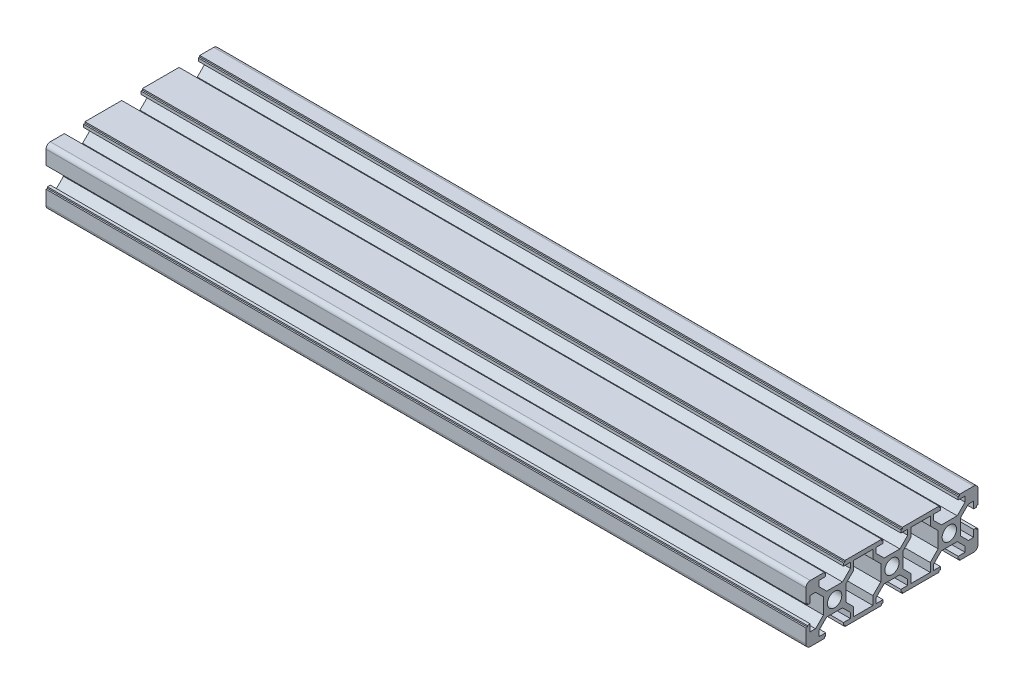
SolidWorks part; units mm, degrees
ref_plane "前视基准面" through (0, 0, 0) normal (0, 0, 1) x (1, 0, 0)
ref_plane "上视基准面" through (0, 0, 0) normal (0, 1, 0) x (1, 0, 0)
ref_plane "右视基准面" through (0, 0, 0) normal (1, 0, 0) x (0, 0, -1)
sketch "草图5" plane through (0, 0, 0) normal (0, 0, 1) x (1, 0, 0)
  line L0 (548.6373, 8.9854) -> (813.6373, 8.9854)
  dimension "D1" = 265
other "铝型材 20 X 20 X R1.5(1)"
ref_plane "基准面2" through (548.6373, 8.9854, 0) normal (1, 0, 0) x (0, 1, 0)
sketch "Sketch1" plane through (548.6373, 8.9854, 0) normal (1, 0, 0) x (0, 1, 0)
  line L0 (-10, -3.6) -> (-9.5, -3.6)
  line L1 (-9.5, -3.6) -> (-9.5, -3.1)
  line L2 (-9.5, -3.1) -> (-8.5, -3.1)
  line L3 (-8.5, -3.1) -> (-8.5, -5.5)
  line L4 (10, -8.5) -> (10, -3.6)
  line L5 (8.5, -10) -> (3.6, -10)
  line L6 (-10, 8.5) -> (-10, 3.6)
  line L7 (-10, 11.5) -> (-10, 8.5)
  line L8 (-14.8756, 0) -> (0, 0) construction
  line L9 (0, 0) -> (0, 14.1675) construction
  line L10 (-8.5, -5.5) -> (-6.65, -5.5)
  line L11 (-6.65, -5.5) -> (-3.9, -2.75)
  line L12 (-3.9, -2.75) -> (-3.9, 2.75)
  line L13 (-6.65, 5.5) -> (-3.9, 2.75)
  line L14 (-8.5, 5.5) -> (-6.65, 5.5)
  line L15 (-8.5, 3.1) -> (-8.5, 5.5)
  line L16 (-9.5, 3.1) -> (-8.5, 3.1)
  line L17 (-9.5, 3.6) -> (-9.5, 3.1)
  line L18 (-10, 3.6) -> (-9.5, 3.6)
  line L19 (-10, -3.6) -> (-10, -8.5)
  line L20 (-5.5, 6.65) -> (-8.5, 6.65)
  line L21 (-8.5, 6.65) -> (-8.5, 13.35)
  line L22 (-8.5, 13.35) -> (-5.5, 13.35)
  line L23 (-5.5, 26.65) -> (-8.5, 26.65)
  line L24 (-8.5, 26.65) -> (-8.5, 33.35)
  line L25 (-5.5, 6.65) -> (-2.75, 3.9)
  line L26 (-2.75, 3.9) -> (2.75, 3.9)
  line L27 (5.5, 6.65) -> (2.75, 3.9)
  line L28 (-8.5, 33.35) -> (-5.5, 33.35)
  line L29 (5.5, 6.65) -> (8.5, 6.65)
  line L30 (8.5, 6.65) -> (8.5, 13.35)
  line L31 (8.5, 13.35) -> (5.5, 13.35)
  line L32 (5.5, 26.65) -> (8.5, 26.65)
  line L33 (10, 3.6) -> (9.5, 3.6)
  line L34 (9.5, 3.6) -> (9.5, 3.1)
  line L35 (9.5, 3.1) -> (8.5, 3.1)
  line L36 (8.5, 3.1) -> (8.5, 5.5)
  line L37 (8.5, 5.5) -> (6.65, 5.5)
  line L38 (6.65, 5.5) -> (3.9, 2.75)
  line L39 (3.9, 2.75) -> (3.9, -2.75)
  line L40 (6.65, -5.5) -> (3.9, -2.75)
  line L41 (8.5, -5.5) -> (6.65, -5.5)
  line L42 (8.5, -3.1) -> (8.5, -5.5)
  line L43 (9.5, -3.1) -> (8.5, -3.1)
  line L44 (9.5, -3.6) -> (9.5, -3.1)
  line L45 (10, -3.6) -> (9.5, -3.6)
  line L46 (3.6, -10) -> (3.6, -9.5)
  line L47 (3.6, -9.5) -> (3.1, -9.5)
  line L48 (3.1, -9.5) -> (3.1, -8.5)
  line L49 (3.1, -8.5) -> (5.5, -8.5)
  line L50 (5.5, -8.5) -> (5.5, -6.65)
  line L51 (5.5, -6.65) -> (2.75, -3.9)
  line L52 (2.75, -3.9) -> (-2.75, -3.9)
  line L53 (-5.5, -6.65) -> (-2.75, -3.9)
  line L54 (-5.5, -8.5) -> (-5.5, -6.65)
  line L55 (-3.1, -8.5) -> (-5.5, -8.5)
  line L56 (-3.1, -9.5) -> (-3.1, -8.5)
  line L57 (-3.6, -9.5) -> (-3.1, -9.5)
  line L58 (-3.6, -10) -> (-3.6, -9.5)
  line L59 (10, 3.6) -> (10, 8.5)
  line L60 (-3.6, -10) -> (-8.5, -10)
  line L61 (-10, 31.5) -> (-10, 28.5)
  line L62 (-10, 16.4) -> (-9.5, 16.4)
  line L63 (-9.5, 16.4) -> (-9.5, 16.9)
  line L64 (-9.5, 16.9) -> (-8.5, 16.9)
  line L65 (-8.5, 16.9) -> (-8.5, 14.5)
  line L66 (10, 11.5) -> (10, 16.4)
  line L67 (10, 31.5) -> (10, 28.5)
  line L68 (-10, 28.5) -> (-10, 23.6)
  line L69 (10, 11.5) -> (10, 8.5)
  line L70 (-8.5, 14.5) -> (-6.65, 14.5)
  line L71 (-6.65, 14.5) -> (-3.9, 17.25)
  line L72 (-3.9, 17.25) -> (-3.9, 22.75)
  line L73 (-6.65, 25.5) -> (-3.9, 22.75)
  line L74 (-8.5, 25.5) -> (-6.65, 25.5)
  line L75 (-8.5, 23.1) -> (-8.5, 25.5)
  line L76 (-9.5, 23.1) -> (-8.5, 23.1)
  line L77 (-9.5, 23.6) -> (-9.5, 23.1)
  line L78 (-10, 23.6) -> (-9.5, 23.6)
  line L79 (-10, 16.4) -> (-10, 11.5)
  line L80 (8.5, 26.65) -> (8.5, 33.35)
  line L81 (8.5, 33.35) -> (5.5, 33.35)
  line L85 (-5.5, 26.65) -> (-2.75, 23.9)
  line L86 (-2.75, 23.9) -> (2.75, 23.9)
  line L87 (5.5, 26.65) -> (2.75, 23.9)
  line L93 (10, 23.6) -> (9.5, 23.6)
  line L94 (9.5, 23.6) -> (9.5, 23.1)
  line L95 (9.5, 23.1) -> (8.5, 23.1)
  line L96 (8.5, 23.1) -> (8.5, 25.5)
  line L97 (8.5, 25.5) -> (6.65, 25.5)
  line L98 (6.65, 25.5) -> (3.9, 22.75)
  line L99 (3.9, 22.75) -> (3.9, 17.25)
  line L100 (6.65, 14.5) -> (3.9, 17.25)
  line L101 (8.5, 14.5) -> (6.65, 14.5)
  line L102 (8.5, 16.9) -> (8.5, 14.5)
  line L103 (9.5, 16.9) -> (8.5, 16.9)
  line L104 (9.5, 16.4) -> (9.5, 16.9)
  line L105 (10, 16.4) -> (9.5, 16.4)
  line L111 (5.5, 13.35) -> (2.75, 16.1)
  line L112 (2.75, 16.1) -> (-2.75, 16.1)
  line L113 (-5.5, 13.35) -> (-2.75, 16.1)
  line L119 (10, 23.6) -> (10, 28.5)
  line L122 (-14.8756, 20) -> (0, 20) construction
  line L123 (0, 20) -> (0, 34.1675) construction
  line L124 (-10, 36.4) -> (-9.5, 36.4)
  line L125 (-9.5, 36.4) -> (-9.5, 36.9)
  line L126 (-9.5, 36.9) -> (-8.5, 36.9)
  line L127 (-8.5, 36.9) -> (-8.5, 34.5)
  line L128 (10, 31.5) -> (10, 36.4)
  line L130 (-10, 48.5) -> (-10, 43.6)
  line L131 (-8.5, 50) -> (-3.6, 50)
  line L132 (-8.5, 34.5) -> (-6.65, 34.5)
  line L133 (-6.65, 34.5) -> (-3.9, 37.25)
  line L134 (-3.9, 37.25) -> (-3.9, 42.75)
  line L135 (-6.65, 45.5) -> (-3.9, 42.75)
  line L136 (-8.5, 45.5) -> (-6.65, 45.5)
  line L137 (-8.5, 43.1) -> (-8.5, 45.5)
  line L138 (-9.5, 43.1) -> (-8.5, 43.1)
  line L139 (-9.5, 43.6) -> (-9.5, 43.1)
  line L140 (-10, 43.6) -> (-9.5, 43.6)
  line L141 (-10, 36.4) -> (-10, 31.5)
  line L142 (-3.6, 50) -> (-3.6, 49.5)
  line L143 (-3.6, 49.5) -> (-3.1, 49.5)
  line L144 (-3.1, 49.5) -> (-3.1, 48.5)
  line L145 (-3.1, 48.5) -> (-5.5, 48.5)
  line L146 (-5.5, 48.5) -> (-5.5, 46.65)
  line L147 (-5.5, 46.65) -> (-2.75, 43.9)
  line L148 (-2.75, 43.9) -> (2.75, 43.9)
  line L149 (5.5, 46.65) -> (2.75, 43.9)
  line L150 (5.5, 48.5) -> (5.5, 46.65)
  line L151 (3.1, 48.5) -> (5.5, 48.5)
  line L152 (3.1, 49.5) -> (3.1, 48.5)
  line L153 (3.6, 49.5) -> (3.1, 49.5)
  line L154 (3.6, 50) -> (3.6, 49.5)
  line L155 (10, 43.6) -> (9.5, 43.6)
  line L156 (9.5, 43.6) -> (9.5, 43.1)
  line L157 (9.5, 43.1) -> (8.5, 43.1)
  line L158 (8.5, 43.1) -> (8.5, 45.5)
  line L159 (8.5, 45.5) -> (6.65, 45.5)
  line L160 (6.65, 45.5) -> (3.9, 42.75)
  line L161 (3.9, 42.75) -> (3.9, 37.25)
  line L162 (6.65, 34.5) -> (3.9, 37.25)
  line L163 (8.5, 34.5) -> (6.65, 34.5)
  line L164 (8.5, 36.9) -> (8.5, 34.5)
  line L165 (9.5, 36.9) -> (8.5, 36.9)
  line L166 (9.5, 36.4) -> (9.5, 36.9)
  line L167 (10, 36.4) -> (9.5, 36.4)
  line L173 (5.5, 33.35) -> (2.75, 36.1)
  line L174 (2.75, 36.1) -> (-2.75, 36.1)
  line L175 (-5.5, 33.35) -> (-2.75, 36.1)
  line L181 (10, 43.6) -> (10, 48.5)
  line L183 (3.6, 50) -> (8.5, 50)
  line L184 (-14.8756, 40) -> (0, 40) construction
  line L185 (0, 40) -> (0, 54.1675) construction
  line L186 (-3.6, 10) -> (-8.5, 10) [skipped]
  line L187 (-3.6, 30) -> (-8.5, 30) [skipped]
  line L188 (8.5, 10) -> (3.6, 10) [skipped]
  line L189 (8.5, 30) -> (3.6, 30) [skipped]
  line L190 (-3.6, 10) -> (-3.6, 9.5) [skipped]
  line L191 (-3.6, 9.5) -> (-3.1, 9.5) [skipped]
  line L192 (-3.1, 9.5) -> (-3.1, 8.5) [skipped]
  line L193 (-3.1, 10.5) -> (-3.1, 11.5) [skipped]
  line L194 (-3.6, 10.5) -> (-3.1, 10.5) [skipped]
  line L195 (-3.6, 10) -> (-3.6, 10.5) [skipped]
  line L196 (-3.1, 11.5) -> (-5.5, 11.5) [skipped]
  line L197 (-3.1, 8.5) -> (-5.5, 8.5) [skipped]
  line L198 (-5.5, 8.5) -> (-5.5, 6.65) [skipped]
  line L199 (-5.5, 11.5) -> (-5.5, 13.35) [skipped]
  line L200 (-5.5, 31.5) -> (-5.5, 33.35) [skipped]
  line L201 (-3.1, 31.5) -> (-5.5, 31.5) [skipped]
  line L202 (-3.1, 30.5) -> (-3.1, 31.5) [skipped]
  line L203 (-3.6, 30.5) -> (-3.1, 30.5) [skipped]
  line L204 (-3.6, 30) -> (-3.6, 30.5) [skipped]
  line L205 (5.5, 8.5) -> (5.5, 6.65) [skipped]
  line L206 (3.1, 8.5) -> (5.5, 8.5) [skipped]
  line L207 (3.1, 9.5) -> (3.1, 8.5) [skipped]
  line L208 (3.6, 9.5) -> (3.1, 9.5) [skipped]
  line L209 (3.6, 10) -> (3.6, 9.5) [skipped]
  line L210 (3.6, 10) -> (3.6, 10.5) [skipped]
  line L211 (3.6, 10.5) -> (3.1, 10.5) [skipped]
  line L212 (3.1, 10.5) -> (3.1, 11.5) [skipped]
  line L213 (3.1, 11.5) -> (5.5, 11.5) [skipped]
  line L214 (5.5, 11.5) -> (5.5, 13.35) [skipped]
  line L215 (3.6, 30) -> (3.6, 30.5) [skipped]
  line L216 (3.6, 30.5) -> (3.1, 30.5) [skipped]
  line L217 (3.1, 30.5) -> (3.1, 31.5) [skipped]
  line L218 (3.1, 31.5) -> (5.5, 31.5) [skipped]
  line L219 (5.5, 31.5) -> (5.5, 33.35) [skipped]
  circle A0 centre (0, 0) radius 2.5
  arc A1 (-8.5, -10) -> (-10, -8.5) centre (-8.5, -8.5) cw
  arc A3 (10, -8.5) -> (8.5, -10) centre (8.5, -8.5) cw
  circle A5 centre (0, 20) radius 2.5
  circle A10 centre (0, 40) radius 2.5
  arc A12 (-8.5, 50) -> (-10, 48.5) centre (-8.5, 48.5) ccw
  arc A14 (10, 48.5) -> (8.5, 50) centre (8.5, 48.5) ccw
  arc A15 (-8.5, 10) -> (-10, 11.5) centre (-8.5, 11.5) cw [skipped]
  arc A16 (-8.5, 30) -> (-10, 31.5) centre (-8.5, 31.5) cw [skipped]
  arc A17 (10, 11.5) -> (8.5, 10) centre (8.5, 11.5) cw [skipped]
  arc A18 (10, 31.5) -> (8.5, 30) centre (8.5, 31.5) cw [skipped]
  point P0 (0, 0)
  point P1 (0, 10)
  point P2 (-10, 0)
  point P3 (0, 0)
  point P4 (0, 0)
  point P5 (10, -10)
  point P6 (10, 10)
  point P7 (-10, 10)
  point P8 (-10, -10)
  point P13 (0, 0)
  point P36 (-10, -10)
  point P39 (-10, 10)
  point P44 (0, 20)
  point P87 (0, 30)
  point P88 (-10, 20)
  point P89 (0, 20)
  point P90 (0, 20)
  point P91 (10, 10)
  point P92 (10, 30)
  point P93 (-10, 30)
  point P94 (-10, 10)
  point P99 (0, 20)
  point P168 (0, 40)
  point P169 (0, 50)
  point P170 (-10, 40)
  point P171 (0, 40)
  point P172 (0, 40)
  point P173 (10, 30)
  point P174 (10, 50)
  point P175 (-10, 50)
  point P176 (-10, 30)
  point P181 (0, 40)
  dimension "D1" = 11
  dimension "D3" = 6.2
  dimension "D4" = 7.2
  dimension "D5" = 6.1
  dimension "D6" = 5
  dimension "D7" = 1.5
  dimension "D8" = 45
  dimension "D9" = 0.5
  dimension "D10" = 1
  dimension "D11" = 5.5
  dimension "D12" = 3
